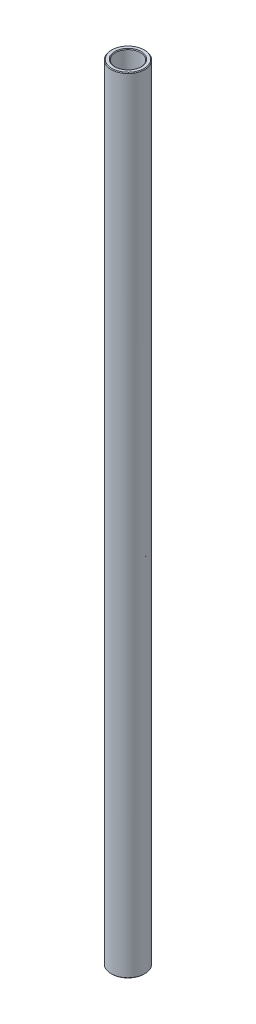
SolidWorks part; units mm, degrees
ref_plane "Front Plane" through (0, 0, 0) normal (0, 0, 1) x (1, 0, 0)
ref_plane "Top Plane" through (0, 0, 0) normal (0, 1, 0) x (1, 0, 0)
ref_plane "Right Plane" through (0, 0, 0) normal (1, 0, 0) x (0, 0, -1)
sketch "Sketch1" plane through (0, 0, 0) normal (0, 0, 1) x (1, 0, 0)
  line L0 (0, 11.6086) -> (0, -11.6086) construction
  line L1 (4.7625, 148.59) -> (6.35, 148.59)
  line L2 (6.35, 148.59) -> (6.35, -148.59)
  line L3 (6.35, -148.59) -> (4.7625, -148.59)
  line L4 (4.7625, -148.59) -> (4.7625, 148.59)
  line L5 (4.7625, 0) -> (0, 0) construction
  dimension "D1" = 9.525
  dimension "D2" = 12.7
  dimension "D3" = 297.18
revolve "Revolve1" add sketch "Sketch1" angle 360 about L0
chamfer "Chamfer1" distance 0.254 angle 45 4 edges at (-4.7625, -148.59, 0) (-6.35, -148.59, 0) (-6.35, 148.59, 0) (-4.7625, 148.59, 0)
